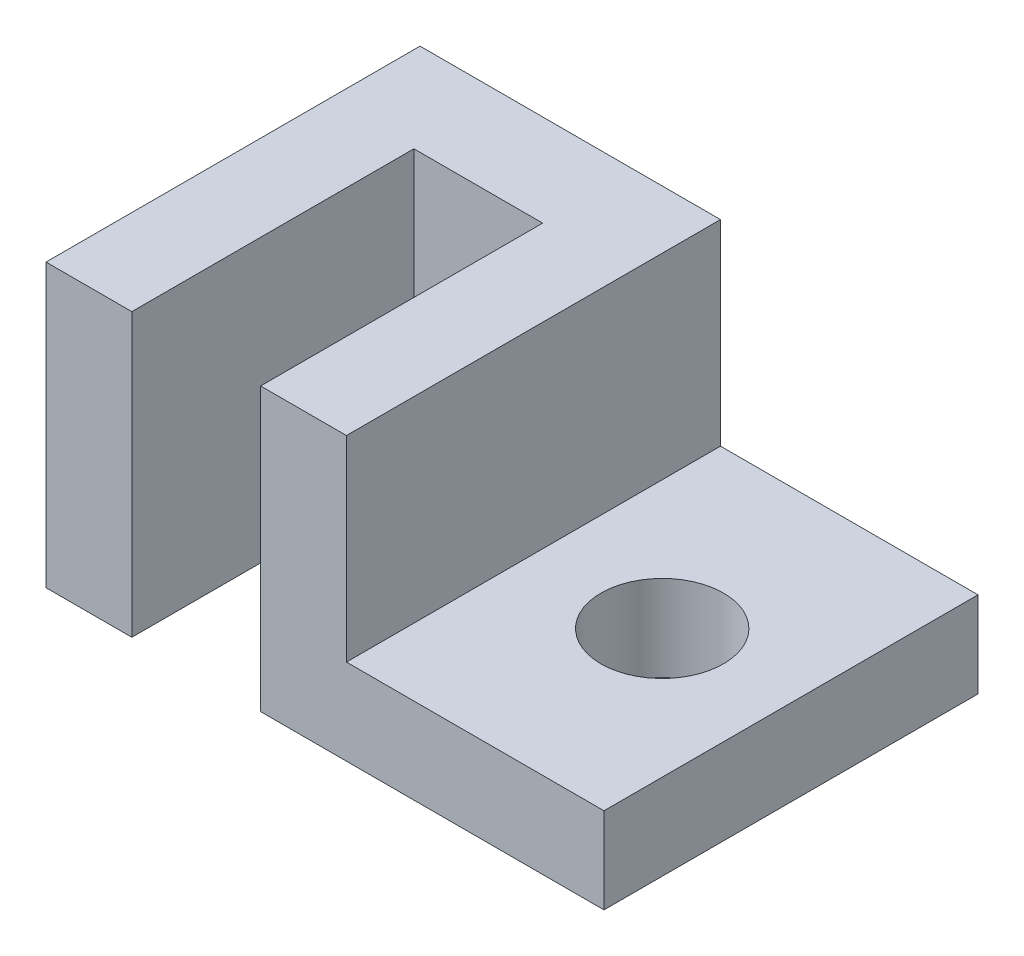
SolidWorks part; units mm, degrees
ref_plane "정면" through (0, 0, 0) normal (0, 0, 1) x (1, 0, 0)
ref_plane "윗면" through (0, 0, 0) normal (0, 1, 0) x (1, 0, 0)
ref_plane "우측면" through (0, 0, 0) normal (1, 0, 0) x (0, 0, -1)
sketch "스케치1" plane through (0, 0, 0) normal (0, 1, 0) x (1, 0, 0)
  line L0 (0, 0) -> (0, 61)
  line L1 (0, 61) -> (49, 61)
  line L2 (49, 61) -> (49, 0)
  line L3 (49, 0) -> (35, 0)
  line L4 (35, 0) -> (35, 46)
  line L5 (35, 46) -> (14, 46)
  line L6 (14, 46) -> (14, 0)
  line L7 (14, 0) -> (0, 0)
  dimension "D1" = 21
  dimension "D2" = 49
  dimension "D3" = 61
  dimension "D4" = 15
extrude "보스-돌출1" add sketch "스케치1" along normal blind 46
sketch "스케치2" plane through (0, 0, 0) normal (0, 1, 0) x (1, 0, 0)
  line L0 (49, 0) -> (49, 61) construction
  line L1 (49, 61) -> (91, 61)
  line L2 (49, 61) -> (49, 0)
  line L3 (49, 0) -> (91, 0)
  line L4 (91, 61) -> (91, 0)
  line L5 (35, 0) -> (49, 0) construction
  circle A0 centre (70, 30.5) radius 10
  dimension "D3" = 20
  dimension "D1" = 42
  dimension "D2" = 61
  dimension "D4" = 21
  dimension "D5" = 30.5
extrude "보스-돌출2" add sketch "스케치2" along normal blind 14
